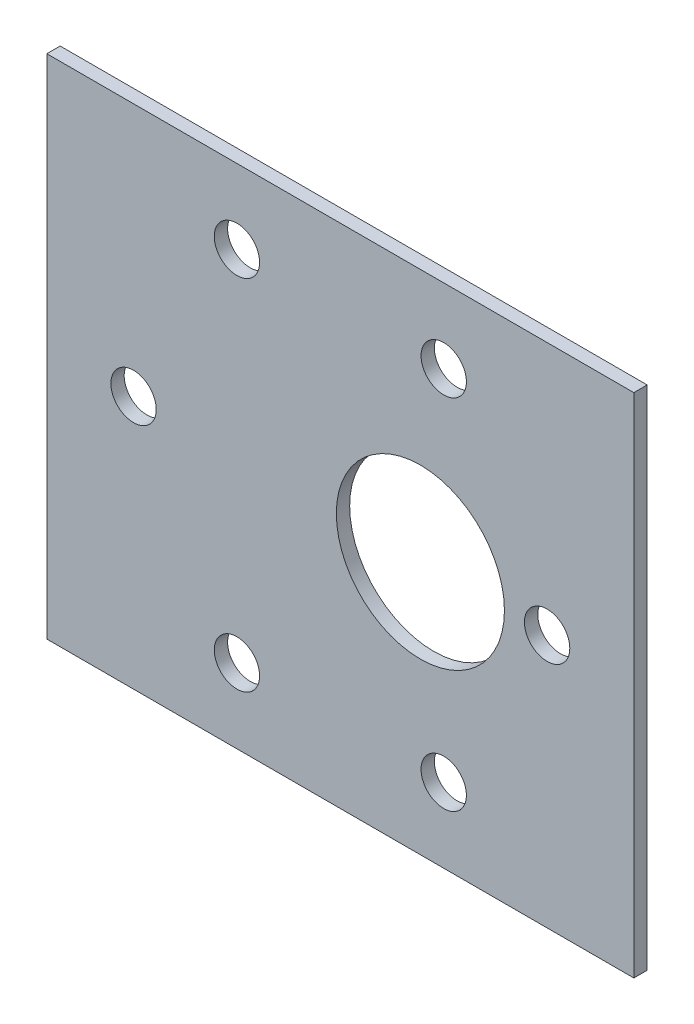
SolidWorks part; units mm, degrees
ref_plane "Front Plane" through (0, 0, 0) normal (0, 0, 1) x (1, 0, 0)
ref_plane "Top Plane" through (0, 0, 0) normal (0, 1, 0) x (1, 0, 0)
ref_plane "Right Plane" through (0, 0, 0) normal (1, 0, 0) x (0, 0, -1)
sketch "Offset housing pattern and shaft bore profile" plane through (0, 0, 0) normal (0, 0, 1) x (1, 0, 0)
  line L0 (-28, 9.5) -> (16, 9.5)
  line L1 (16, 9.5) -> (16, 47.5)
  line L2 (16, 47.5) -> (-28, 47.5)
  line L3 (-28, 47.5) -> (-28, 9.5)
  circle A0 centre (0, 28.5) radius 6.3
  circle A1 centre (9.5, 28.5) radius 1.7
  circle A2 centre (1.75, 41.9234) radius 1.7
  circle A3 centre (-13.75, 41.9234) radius 1.7
  circle A4 centre (-21.5, 28.5) radius 1.7
  circle A5 centre (-13.75, 15.0766) radius 1.7
  circle A6 centre (1.75, 15.0766) radius 1.7
extrude "Offset housing pattern and shaft bore" add sketch "Offset housing pattern and shaft bore profile" along normal blind 1
